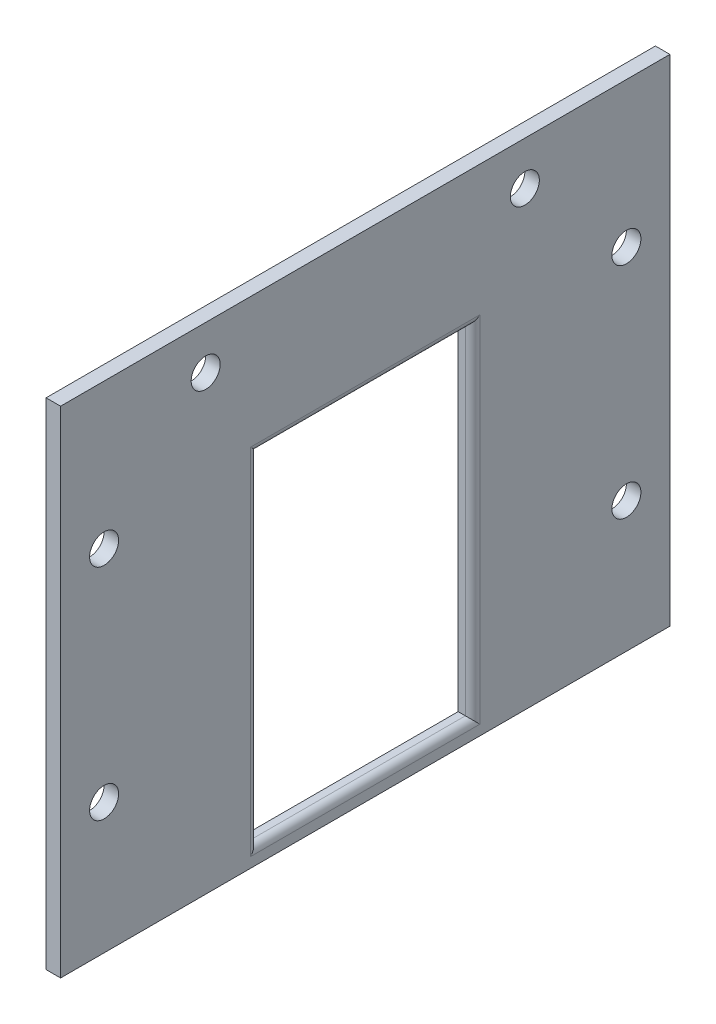
SolidWorks part; units mm, degrees
material "6061-T6 (SS)"
ref_plane "Front Plane" through (0, 0, 0) normal (0, 0, 1) x (1, 0, 0)
ref_plane "Top Plane" through (0, 0, 0) normal (0, 1, 0) x (1, 0, 0)
ref_plane "Right Plane" through (0, 0, 0) normal (1, 0, 0) x (0, 0, -1)
sketch "Sketch1" plane through (0, 0, 0) normal (1, 0, 0) x (0, 0, -1)
  line L1 (-63.5, -88.9) -> (63.5, -88.9)
  line L2 (-63.5, -88.9) -> (-63.5, 88.9)
  line L3 (-63.5, 88.9) -> (63.5, 88.9)
  line L4 (63.5, -88.9) -> (63.5, 88.9)
  line L5 (-63.5, -88.9) -> (63.5, 88.9) construction
  line L6 (-63.5, 88.9) -> (63.5, -88.9) construction
  point P0 (0, 0)
  dimension "D1" = 127
  dimension "D2" = 177.8
extrude "Boss-Extrude1" add sketch "Sketch1" against normal blind 3.175 contours L3 L4 L1 L2
sketch "Sketch7" plane through (0, 0, 0) normal (1, 0, 0) x (0, 0, -1)
  line L0 (63.5, -88.9) -> (63.5, 88.9) construction
  line L1 (-63.5, 88.9) -> (63.5, 88.9)
  line L2 (-63.5, 88.9) -> (-63.5, 19.475)
  line L3 (-63.5, 19.475) -> (63.5, 19.475)
  line L4 (63.5, 88.9) -> (63.5, 19.475)
  line L5 (-63.5, 88.9) -> (63.5, 88.9) construction
  dimension "D1" = 69.425
  dimension "D2" = 0
extrude "Cut-Extrude5" cut sketch "Sketch7" against normal through all
sketch "Sketch8" plane through (0, 0, 0) normal (1, 0, 0) x (0, 0, -1)
  line L0 (-63.5, -88.9) -> (63.5, -88.9) construction
  line L1 (-63.5, 19.475) -> (-66.675, 19.475)
  line L2 (-63.5, 19.475) -> (-63.5, -88.9)
  line L3 (-63.5, -88.9) -> (-66.675, -88.9)
  line L4 (-66.675, 19.475) -> (-66.675, -88.9)
  line L6 (63.5, -88.9) -> (66.675, -88.9)
  line L7 (63.5, -88.9) -> (63.5, 19.475)
  line L8 (63.5, 19.475) -> (66.675, 19.475)
  line L9 (66.675, -88.9) -> (66.675, 19.475)
  dimension "D1" = 0
  dimension "D2" = 3.175
  dimension "D3" = 3.175
extrude "Boss-Extrude2" add sketch "Sketch8" against normal up to surface (3.175 mm away) up to face at (-3.175, -34.7125, 0)
sketch "Sketch9" plane through (0, 0, 0) normal (1, 0, 0) x (0, 0, -1)
  line L0 (0, -88.9) -> (0, -85.09) construction
  line L1 (-66.675, -88.9) -> (66.675, -88.9) construction
  line L3 (23.495, -85.09) -> (23.495, -10.668)
  line L7 (23.495, -85.09) -> (-23.495, -85.09)
  line L8 (-23.495, -85.09) -> (-23.495, -10.668)
  line L9 (-23.495, -10.668) -> (23.495, -10.668)
  dimension "D1" = 23.495
  dimension "D2" = 74.422
  dimension "D3" = 23.495
extrude "Cut-Extrude6" cut sketch "Sketch9" against normal through all
fillet "Fillet1" radius 1.5875 4 edges at (0, -47.879, -23.495) (0, -85.09, 0) (0, -10.668, 0) (0, -47.879, 23.495)
sketch "Sketch10" plane through (0, 0, 0) normal (1, 0, 0) x (0, 0, -1)
  line L0 (-66.675, 19.475) -> (-66.675, -88.9) construction
  line L1 (-66.675, -88.9) -> (66.675, -88.9) construction
  line L2 (-66.675, 19.475) -> (66.675, 19.475) construction
  line L3 (0, 19.475) -> (0, -88.9) construction
  circle A0 centre (-57.15, -60.325) radius 3.175
  circle A1 centre (-57.15, -12.275) radius 3.175
  circle A2 centre (-34.925, 9.95) radius 3.175
  circle A3 centre (34.925, 9.95) radius 3.175
  circle A4 centre (57.15, -12.275) radius 3.175
  circle A5 centre (57.15, -60.325) radius 3.175
  dimension "D1" = 6.35
  dimension "D4" = 6.35
  dimension "D6" = 6.35
  dimension "D2" = 9.525
  dimension "D3" = 28.575
  dimension "D5" = 31.75
  dimension "D7" = 9.525
  dimension "D8" = 31.75
  dimension "D9" = 0
extrude "Cut-Extrude7" cut sketch "Sketch10" against normal through all
